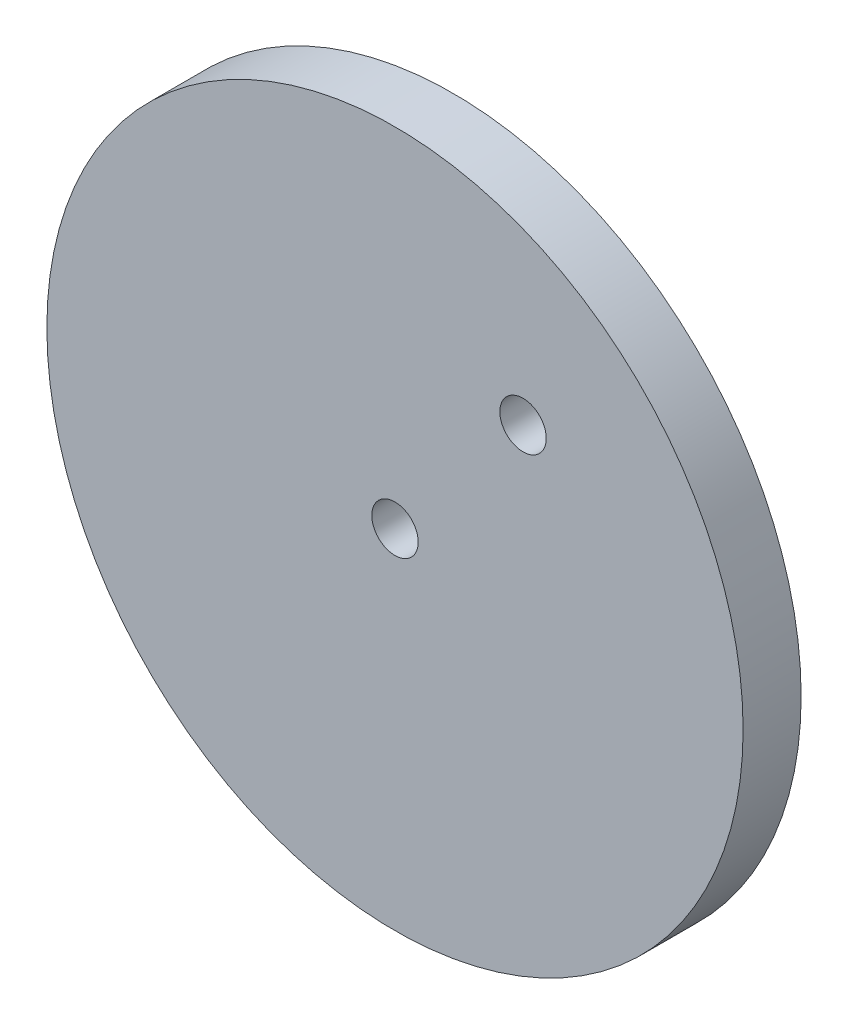
SolidWorks part; units mm, degrees
ref_plane "前视基准面" through (0, 0, 0) normal (0, 0, 1) x (1, 0, 0)
ref_plane "上视基准面" through (0, 0, 0) normal (0, 1, 0) x (1, 0, 0)
ref_plane "右视基准面" through (0, 0, 0) normal (1, 0, 0) x (0, 0, -1)
sketch "草图1" plane through (0, 0, 0) normal (0, 0, 1) x (1, 0, 0)
  circle A0 centre (0, 0) radius 30
extrude "凸台-拉伸1" add sketch "草图1" along normal blind 5
sketch "草图2" plane through (0, 0, 5) normal (0, 0, 1) x (1, 0, 0)
  circle A0 centre (0, 0) radius 2
  circle A1 centre (11.0353, 13.2584) radius 2
  dimension "D1" = 17.25
extrude "切除-拉伸1" cut sketch "草图2" against normal blind 5
